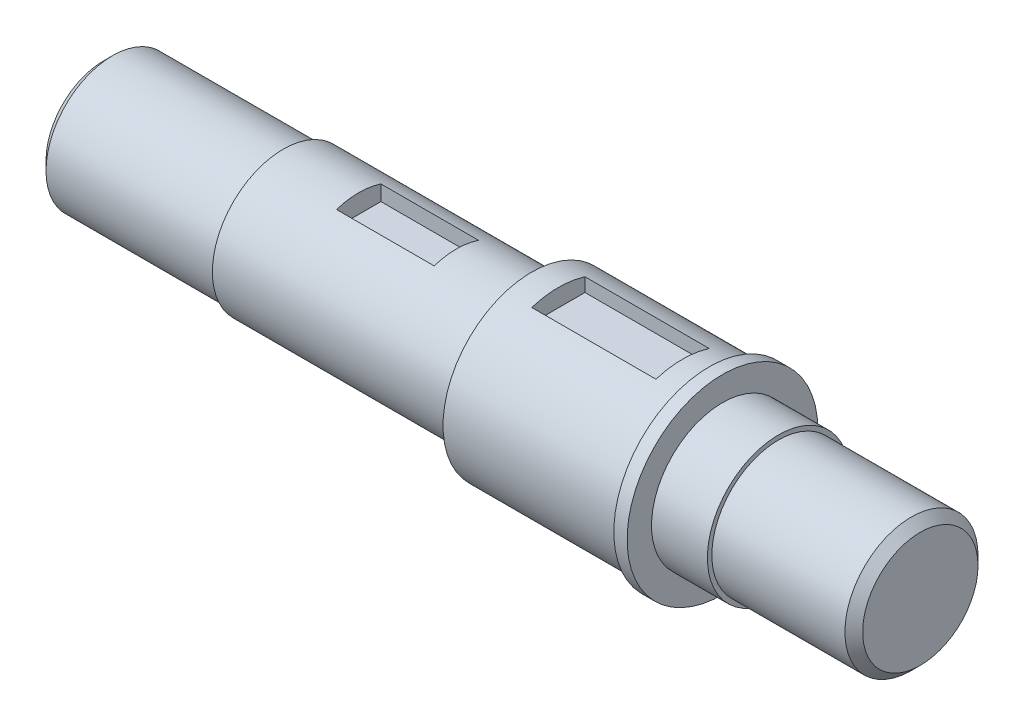
SolidWorks part; units mm, degrees
ref_plane "前视基准面" through (0, 0, 0) normal (0, 0, 1) x (1, 0, 0)
ref_plane "上视基准面" through (0, 0, 0) normal (0, 1, 0) x (1, 0, 0)
ref_plane "右视基准面" through (0, 0, 0) normal (1, 0, 0) x (0, 0, -1)
sketch "草图2" plane through (0, 0, 0) normal (0, 1, 0) x (1, 0, 0)
  line L0 (0, 0) -> (0, 15)
  line L1 (0, 15) -> (40.5, 15)
  line L2 (40.5, 15) -> (40.5, 16)
  line L3 (40.5, 16) -> (96.5, 16)
  line L4 (96.5, 16) -> (96.5, 20)
  line L5 (96.5, 20) -> (136.5, 20)
  line L6 (136.5, 20) -> (136.5, 21.5)
  line L7 (136.5, 21.5) -> (139.5, 21.5)
  line L8 (139.5, 21.5) -> (139.5, 16)
  line L9 (139.5, 16) -> (152.1, 16)
  line L10 (152.1, 16) -> (152.1, 15)
  line L11 (152.1, 15) -> (184.1, 15)
  line L12 (184.1, 15) -> (184.1, 0)
  line L13 (184.1, 0) -> (0, 0)
  dimension "D1" = 15
  dimension "D2" = 40.5
  dimension "D3" = 16
  dimension "D4" = 20
  dimension "D5" = 1.5
  dimension "D6" = 3
  dimension "D7" = 32
  dimension "D8" = 15
  dimension "D9" = 56
  dimension "D10" = 40
  dimension "D11" = 12.6
revolve "旋转1" add sketch "草图2" angle 360 about L13
chamfer "倒角1" distance 2 angle 45 2 edges at (184.1, 0, -15) (0, 0, -15)
sketch "草图3" plane through (0, 0, 0) normal (0, 1, 0) x (1, 0, 0)
  line L0 (0, 0) -> (40.5, 0)
  line L1 (40.5, 15) -> (40.5, -15) construction
  line L2 (40.5, 0) -> (96.5, 0)
  line L3 (96.5, 20) -> (96.5, -20) construction
  line L5 (57.5, 5) -> (79.5, 5)
  line L6 (57.5, 5) -> (57.5, -5)
  line L7 (57.5, -5) -> (79.5, -5)
  line L8 (79.5, 5) -> (79.5, -5)
  line L9 (68.5, -5) -> (68.5, 5) construction
  line L10 (57.5, 0) -> (79.5, 0) construction
  point P5 (68.5, 0)
  dimension "D1" = 22
  dimension "D2" = 10
extrude "切除-拉伸1" cut sketch "草图3" along normal blind 25 from offset 11.75 contours L8 L5 L6 L2 | L8 L2 L6 L7
sketch "草图4" plane through (0, 0, 0) normal (0, 1, 0) x (1, 0, 0)
  line L0 (96.5, 0) -> (136.5, 0)
  line L1 (96.5, 20) -> (96.5, -20) construction
  line L2 (136.5, 20) -> (136.5, -20) construction
  line L4 (102.5, 6) -> (130.5, 6)
  line L5 (102.5, 6) -> (102.5, -6)
  line L6 (102.5, -6) -> (130.5, -6)
  line L7 (130.5, 6) -> (130.5, -6)
  line L8 (116.5, -6) -> (116.5, 6) construction
  line L9 (102.5, 0) -> (130.5, 0) construction
  point P6 (116.5, 0)
  dimension "D1" = 28
  dimension "D2" = 12
extrude "切除-拉伸2" cut sketch "草图4" along normal blind 11 from offset 16 contours L7 L4 L5 L0 | L7 L0 L5 L6
